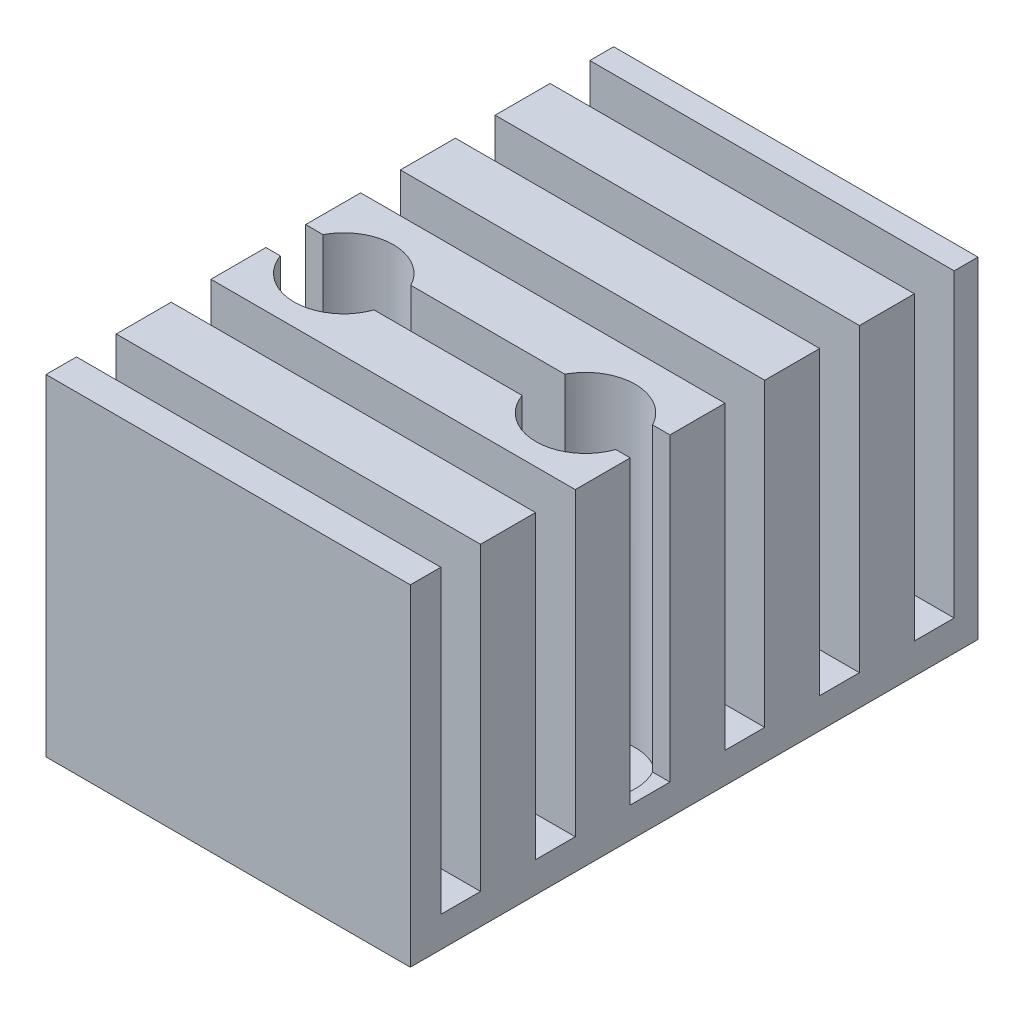
SolidWorks part; units mm, degrees
ref_plane "Front Plane" through (0, 0, 0) normal (0, 0, 1) x (1, 0, 0)
ref_plane "Top Plane" through (0, 0, 0) normal (0, 1, 0) x (1, 0, 0)
ref_plane "Right Plane" through (0, 0, 0) normal (1, 0, 0) x (0, 0, -1)
sketch "Sketch1" plane through (0, 0, 0) normal (0, 1, 0) x (1, 0, 0)
  line L0 (0, 0) -> (0, -1.43) construction
  line L1 (-5.5, -8.57) -> (5.5, -8.57)
  line L2 (-5.5, -8.57) -> (-5.5, 8.57)
  line L3 (-5.5, 8.57) -> (5.5, 8.57)
  line L4 (5.5, -8.57) -> (5.5, 8.57)
  line L5 (-5.5, -8.57) -> (5.5, 8.57) construction
  line L6 (-5.5, 8.57) -> (5.5, -8.57) construction
  line L7 (-3.65, -1.43) -> (3.65, -1.43) construction
  circle A0 centre (3.65, -1.43) radius 0.8
  circle A1 centre (-3.65, -1.43) radius 0.8
  point P0 (0, 0)
  point P10 (0, -1.43)
  dimension "D5" = 1.6
  dimension "D6" = 1.6
  dimension "D1" = 11
  dimension "D2" = 17.14
  dimension "D3" = 7.3
  dimension "D4" = 7.14
extrude "Boss-Extrude1" add sketch "Sketch1" along normal blind 10
sketch "Sketch3" plane through (5.5, 0, 0) normal (1, 0, 0) x (0, 0, -1)
  line L0 (0, 0) -> (0, 10) construction
  line L1 (-8.57, 10) -> (8.57, 10) construction
  line L2 (-1.43, 10) -> (-1.43, 0) construction
  line L3 (-8.57, 0) -> (8.57, 0) construction
  line L4 (-8.57, 10) -> (-8.57, 0) construction
  line L5 (-4.29, 10) -> (-4.29, 0) construction
  line L6 (-7.15, 10) -> (-7.15, 0) construction
  line L7 (7.15, 10) -> (7.15, 0) construction
  line L8 (4.29, 10) -> (4.29, 0) construction
  line L9 (1.43, 10) -> (1.43, 0) construction
  line L10 (-4.79, 10) -> (-4.79, 0.9222)
  line L11 (-7.65, 10) -> (-6.45, 10)
  line L12 (-7.65, 10) -> (-7.65, 0.9222)
  line L13 (-7.65, 0.9222) -> (-6.45, 0.9222)
  line L14 (-6.45, 10) -> (-6.45, 0.9222)
  line L15 (-3.59, 10) -> (-3.59, 0.9222)
  line L16 (-4.79, 0.9222) -> (-3.59, 0.9222)
  line L17 (-4.79, 10) -> (-3.59, 10)
  line L18 (-1.93, 10) -> (-1.93, 0.9222)
  line L19 (-0.73, 10) -> (-0.73, 0.9222)
  line L20 (-1.93, 0.9222) -> (-0.73, 0.9222)
  line L21 (-1.93, 10) -> (-0.73, 10)
  line L22 (0.93, 10) -> (0.93, 0.9222)
  line L23 (2.13, 10) -> (2.13, 0.9222)
  line L24 (0.93, 0.9222) -> (2.13, 0.9222)
  line L25 (0.93, 10) -> (2.13, 10)
  line L26 (3.79, 10) -> (3.79, 0.9222)
  line L27 (4.99, 10) -> (4.99, 0.9222)
  line L28 (3.79, 0.9222) -> (4.99, 0.9222)
  line L29 (3.79, 10) -> (4.99, 10)
  line L30 (6.65, 10) -> (6.65, 0.9222)
  line L31 (7.85, 10) -> (7.85, 0.9222)
  line L32 (6.65, 0.9222) -> (7.85, 0.9222)
  line L33 (6.65, 10) -> (7.85, 10)
  dimension "D1" = 7.14
  dimension "D2" = 3
  dimension "D3" = 2.86
  dimension "D4" = 0.7
  dimension "D5" = 0.5
extrude "Cut-Extrude1" cut sketch "Sketch3" against normal through all
sketch "Sketch4" plane through (0, 10, 0) normal (0, 1, 0) x (1, 0, 0)
  circle A0 centre (-3.65, -1.43) radius 1.5
  circle A1 centre (3.65, -1.43) radius 1.5
  dimension "D1" = 3
  dimension "D2" = 3
extrude "Cut-Extrude2" cut sketch "Sketch4" against normal blind 9.5
